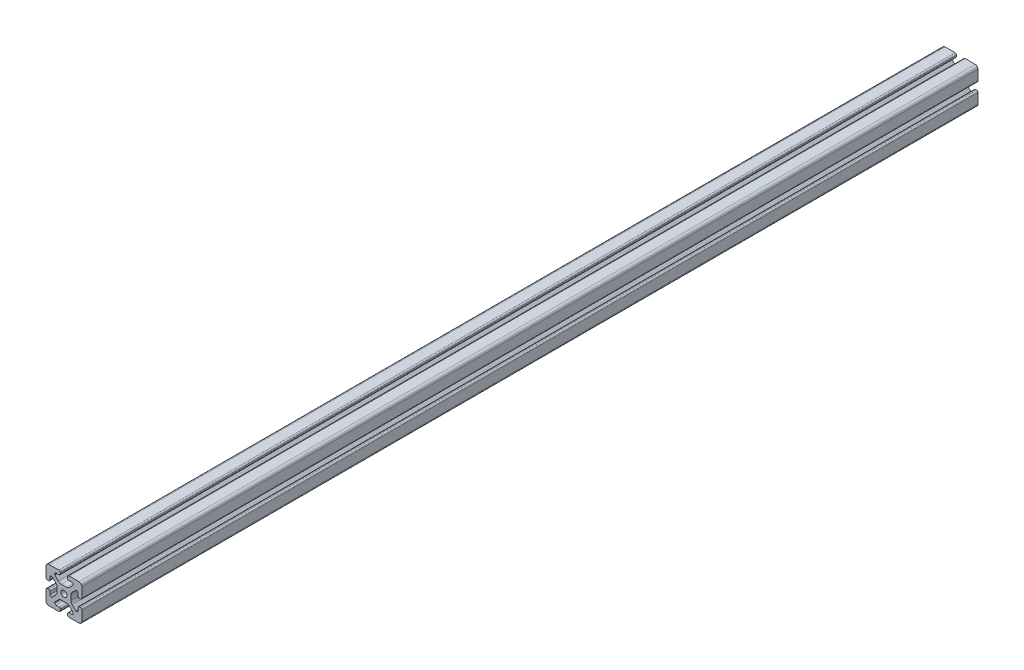
SolidWorks part; units mm, degrees
material "6061 Alloy"
ref_plane "Front Plane" through (0, 0, 0) normal (0, 0, 1) x (1, 0, 0)
ref_plane "Top Plane" through (0, 0, 0) normal (0, 1, 0) x (1, 0, 0)
ref_plane "Right Plane" through (0, 0, 0) normal (1, 0, 0) x (0, 0, -1)
sketch "Sketch1" plane through (0, 0, 0) normal (0, 0, 1) x (1, 0, 0)
  line L0 (0, 19.7407) -> (0, -19.7407) construction
  line L1 (19.0335, 0) -> (-20.7246, 0) construction
  line L2 (-8.715, -15.5246) -> (-5.63, -15.5246)
  line L3 (-10.285, -13.9546) -> (-10.285, -13.4925)
  line L4 (-6.2171, -9.1098) -> (-10.0624, -12.9551)
  line L5 (2.7773, -7.685) -> (-2.7773, -7.685)
  line L6 (10.0624, -12.9551) -> (6.2171, -9.1098)
  line L7 (10.285, -13.9546) -> (10.285, -13.4925)
  line L8 (5.63, -15.5246) -> (8.715, -15.5246)
  line L9 (4.06, -18.43) -> (4.06, -17.0946)
  line L10 (-4.06, -18.43) -> (-4.06, -17.0946)
  line L11 (15.68, -8.7154) -> (15.68, -5.63)
  line L12 (-14.11, -10.2854) -> (-13.8169, -10.2854)
  line L13 (20, -16.83) -> (20, -5.63)
  line L14 (20, 5.63) -> (20, 13.0011)
  line L15 (-16.83, 20) -> (-5.63, 20)
  line L16 (5.63, 20) -> (12.9796, 20)
  line L18 (-8.715, 15.5246) -> (-5.63, 15.5246)
  line L19 (-20, -17.0184) -> (-20, -5.7579)
  line L20 (-20, 5.573) -> (-20, 13.0045)
  line L21 (-15.68, -8.7154) -> (-15.68, -5.7579)
  line L23 (-16.6746, -20) -> (-5.63, -20)
  line L24 (5.63, -20) -> (13, -20)
  line L53 (14.11, -10.2854) -> (13.6201, -10.2854)
  line L54 (13.1637, -9.947) -> (9.0762, -5.8595)
  line L55 (7.685, -2.5008) -> (7.685, 2.5008)
  line L56 (9.0762, 5.8595) -> (13.2795, 10.0628)
  line L57 (13.8169, 10.2854) -> (14.11, 10.2854)
  line L58 (15.68, 8.7154) -> (15.68, 5.63)
  line L59 (17.25, 4.06) -> (18.43, 4.06)
  line L61 (20, 13.0011) -> (20, 16.83)
  line L62 (16.83, 20) -> (12.9796, 20)
  line L64 (4.06, 18.43) -> (4.06, 17.0946)
  line L65 (5.63, 15.5246) -> (8.715, 15.5246)
  line L66 (10.285, 13.9546) -> (10.285, 13.4925)
  line L67 (10.0624, 12.9551) -> (6.2171, 9.1098)
  line L68 (2.7773, 7.685) -> (-2.7773, 7.685)
  line L69 (-6.2171, 9.1098) -> (-10.0624, 12.9551)
  line L70 (-10.285, 13.4925) -> (-10.285, 13.9546)
  line L72 (-4.06, 17.0946) -> (-4.06, 18.43)
  line L75 (-20, 16.83) -> (-20, 13.0045)
  line L77 (-18.43, 4.003) -> (-17.25, 4.003)
  line L78 (-15.68, 5.573) -> (-15.68, 8.4757)
  line L79 (-14.0552, 10.0447) -> (-13.7199, 10.033)
  line L80 (-13.0405, 9.8238) -> (-9.0762, 5.8595)
  line L81 (-7.685, 2.5008) -> (-7.685, -2.5008)
  line L82 (-9.0762, -5.8595) -> (-13.2795, -10.0628)
  line L85 (-17.25, -4.1204) -> (-18.43, -4.1204)
  line L100 (13, -20) -> (16.83, -20)
  line L103 (18.43, -4.06) -> (17.25, -4.06)
  arc A0 (-5.63, -15.5246) -> (-4.06, -17.0946) centre (-5.63, -17.0946) cw
  arc A1 (-8.715, -15.5246) -> (-10.285, -13.9546) centre (-8.715, -13.9546) cw
  arc A2 (-10.285, -13.4925) -> (-10.0624, -12.9551) centre (-9.525, -13.4925) cw
  arc A3 (-6.2171, -9.1098) -> (-2.7773, -7.685) centre (-2.7773, -12.5496) cw
  arc A4 (2.7773, -7.685) -> (6.2171, -9.1098) centre (2.7773, -12.5496) cw
  arc A5 (10.0624, -12.9551) -> (10.285, -13.4925) centre (9.525, -13.4925) cw
  arc A6 (10.285, -13.9546) -> (8.715, -15.5246) centre (8.715, -13.9546) cw
  arc A7 (4.06, -17.0946) -> (5.63, -15.5246) centre (5.63, -17.0946) cw
  arc A8 (5.63, -20) -> (4.06, -18.43) centre (5.63, -18.43) cw
  arc A9 (-4.06, -18.43) -> (-5.63, -20) centre (-5.63, -18.43) cw
  circle A45 centre (0, 0) radius 3.4
  arc A46 (17.25, -4.06) -> (15.68, -5.63) centre (17.25, -5.63) ccw
  arc A47 (14.11, -10.2854) -> (15.68, -8.7154) centre (14.11, -8.7154) ccw
  arc A48 (13.1637, -9.947) -> (13.6201, -10.2854) centre (13.8117, -9.55) ccw
  arc A49 (7.685, -2.5008) -> (9.0762, -5.8595) centre (12.435, -2.5008) ccw
  arc A50 (9.0762, 5.8595) -> (7.685, 2.5008) centre (12.435, 2.5008) ccw
  arc A51 (13.8169, 10.2854) -> (13.2795, 10.0628) centre (13.8169, 9.5254) ccw
  arc A52 (15.68, 8.7154) -> (14.11, 10.2854) centre (14.11, 8.7154) ccw
  arc A53 (15.68, 5.63) -> (17.25, 4.06) centre (17.25, 5.63) ccw
  arc A54 (18.43, 4.06) -> (20, 5.63) centre (18.43, 5.63) ccw
  arc A55 (20, 16.83) -> (16.83, 20) centre (16.83, 16.83) ccw
  arc A56 (5.63, 20) -> (4.06, 18.43) centre (5.63, 18.43) ccw
  arc A57 (4.06, 17.0946) -> (5.63, 15.5246) centre (5.63, 17.0946) ccw
  arc A58 (10.285, 13.9546) -> (8.715, 15.5246) centre (8.715, 13.9546) ccw
  arc A59 (10.0624, 12.9551) -> (10.285, 13.4925) centre (9.525, 13.4925) ccw
  arc A60 (2.7773, 7.685) -> (6.2171, 9.1098) centre (2.7773, 12.5496) ccw
  arc A61 (-6.2171, 9.1098) -> (-2.7773, 7.685) centre (-2.7773, 12.5496) ccw
  arc A62 (-10.285, 13.4925) -> (-10.0624, 12.9551) centre (-9.525, 13.4925) ccw
  arc A63 (-8.715, 15.5246) -> (-10.285, 13.9546) centre (-8.715, 13.9546) ccw
  arc A64 (-5.63, 15.5246) -> (-4.06, 17.0946) centre (-5.63, 17.0946) ccw
  arc A65 (-4.06, 18.43) -> (-5.63, 20) centre (-5.63, 18.43) ccw
  arc A66 (-16.83, 20) -> (-20, 16.83) centre (-16.83, 16.83) ccw
  arc A67 (-20, 5.573) -> (-18.43, 4.003) centre (-18.43, 5.573) ccw
  arc A68 (-17.25, 4.003) -> (-15.68, 5.573) centre (-17.25, 5.573) ccw
  arc A69 (-14.0552, 10.0447) -> (-15.68, 8.4757) centre (-14.11, 8.4757) ccw
  arc A70 (-13.0405, 9.8238) -> (-13.7199, 10.033) centre (-13.5779, 9.2864) ccw
  arc A71 (-7.685, 2.5008) -> (-9.0762, 5.8595) centre (-12.435, 2.5008) ccw
  arc A72 (-9.0762, -5.8595) -> (-7.685, -2.5008) centre (-12.435, -2.5008) ccw
  arc A73 (-13.8169, -10.2854) -> (-13.2795, -10.0628) centre (-13.8169, -9.5254) ccw
  arc A74 (-15.68, -8.7154) -> (-14.11, -10.2854) centre (-14.11, -8.7154) ccw
  arc A75 (-15.68, -5.7579) -> (-17.25, -4.1204) centre (-17.2485, -5.6904) ccw
  arc A76 (-18.43, -4.1204) -> (-20, -5.7579) centre (-18.4315, -5.6904) ccw
  arc A77 (-20, -17.0184) -> (-16.6746, -20) centre (-16.8354, -16.8341) ccw
  arc A88 (16.83, -20) -> (20, -16.83) centre (16.83, -16.83) ccw
  arc A89 (20, -5.63) -> (18.43, -4.06) centre (18.43, -5.63) ccw
  dimension "D2" = 6.8
  dimension "D7" = 20.57
  dimension "D1" = 40
  dimension "D3" = 4.32
  dimension "D4" = 15.37
  dimension "D5" = 20
  dimension "D6" = 4.32
  dimension "D9" = 15.37
extrude "Extrude1" add sketch "Sketch1" against normal blind 1000
equation "\"PinDiameter\"= 0"
equation "\"WallThickness\"= 0.5cm"
equation "\"BottomPlateX\"= 100cm"
equation "\"BottomPlateZ\"= 70cm"
equation "\"BottomPlateHoleD\"=((\"ArmPlateX\")^2+(\"ArmPlateDepth\")^2)^.5+ 10mm"
equation "\"ActuatorL\"= 35cm"
equation "\"ActuatorPinD\"= 6.35mm"
equation "\"ActuatorPinL\"= 15cm"
equation "\"Box-X\"= 40cm"
equation "\"Box-Z\"= 20cm"
equation "\"Box-Y\"= 30cm"
equation "\"ArmPlateThickness\"= 1cm"
equation "\"ArmPlateX\"= 50cm"
equation "\"ArmPlateDepth\"= 20cm"
equation "\"Arm1X\"= 5cm"
equation "\"Arm1L\"= 60cm"
equation "\"Arm2GAP\"= 5cm"
equation "\"Arm2L\"= 60cm"
equation "\"Arm2H\"= 5cm"
equation "\"Arm2Extension\"= 5cm"
equation "\"Arm3GAP\"= 5cm"
equation "\"Arm3L\"= 60cm"
equation "\"Arm3H\"= 5cm"
equation "\"Pin1-2L\"= \"Arm2GAP\" + (2 * \"WallThickness\")"
equation "\"Pin2-3L\"= \"Arm3GAP\" + (4 * \"WallThickness\")"
equation "\"DCMotor1D\"= 65mm"
equation "\"DCMotor1L\"= 215mm"
equation "\"DCMotor1ShaftL\"= 30mm"
equation "\"DCMotor2X\"= 68mm"
equation "\"DCMotor2D\"= 65mm"
equation "\"DCMotor2L\"= 215mm"
equation "\"DCMotor2ShaftL\"= 30mm"
equation "\"DCMotor2ShaftD\"= 15mm"
equation "\"BenchDepth\"= 5cm"
equation "\"BenchH\"= 10cm"
equation "\"BenchL\"= 15cm"
equation "\"PillowBlockW\"= 5cm"
equation "\"PillowBlockCenterH\"= \"DCMotor2X\"/2"
equation "\"EncoderRadius\"= 19mm"
equation "\"EncoderShaftL\"= 15mm"
equation "\"EncoderL\"= 33mm"
equation "\"EncoderHousingThickness\"= 7.5mm"
equation "\"TurntableID\"= 70mm"
equation "\"TurntableInner2*t\" = (\"TurntableOD\"-\"TurntableID\")*.25 - .5mm"
equation "\"TurntableInnerHoleRadius\"= \"TurntableID\"*.5 + \"TurntableInner2*t\"*.5"
equation "\"TurntableOD\"= 120mm"
equation "\"TurntableOuterHoleRadius\" = \"TurntableOD\"*.5 - ((\"TurntableOD\"-\"TurntableID\")*.25-.5mm)*.5"
equation "\"LENGTH@Extrude1\"=\"BottomPlateX\""
